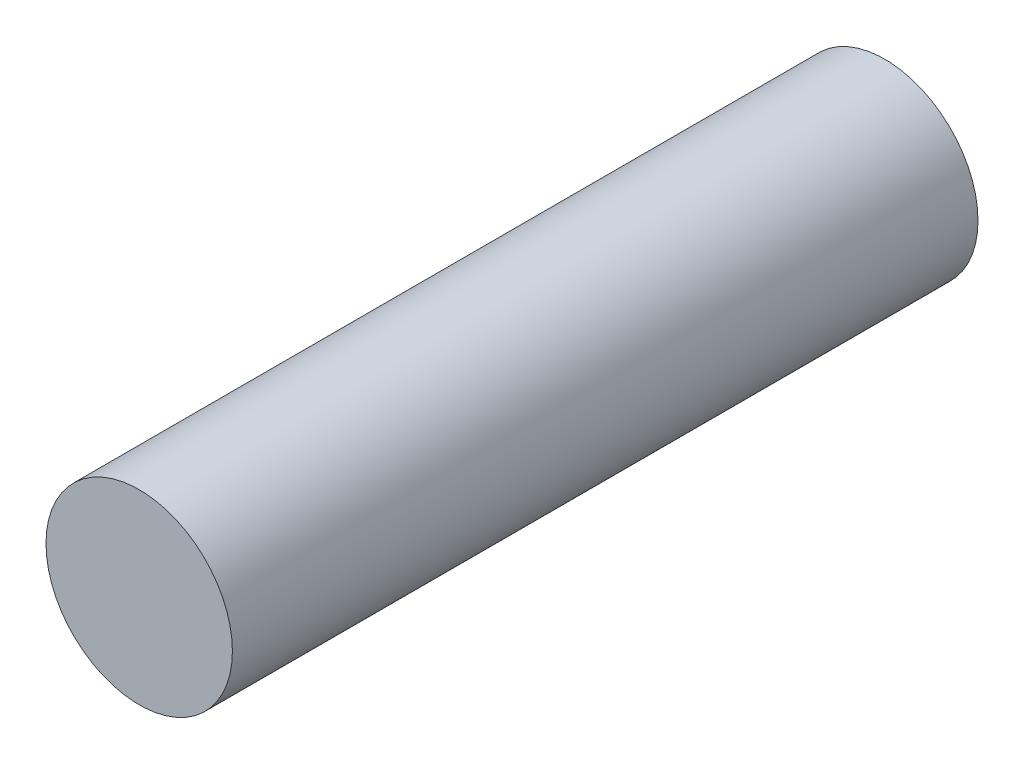
SolidWorks part; units mm, degrees
ref_plane "前视基准面" through (0, 0, 0) normal (0, 0, 1) x (1, 0, 0)
ref_plane "上视基准面" through (0, 0, 0) normal (0, 1, 0) x (1, 0, 0)
ref_plane "右视基准面" through (0, 0, 0) normal (1, 0, 0) x (0, 0, -1)
sketch "草图1" plane through (0, 0, 0) normal (0, 0, 1) x (1, 0, 0)
  circle A0 centre (0, 0) radius 1.75
extrude "凸台-拉伸1" add sketch "草图1" along normal blind 14
